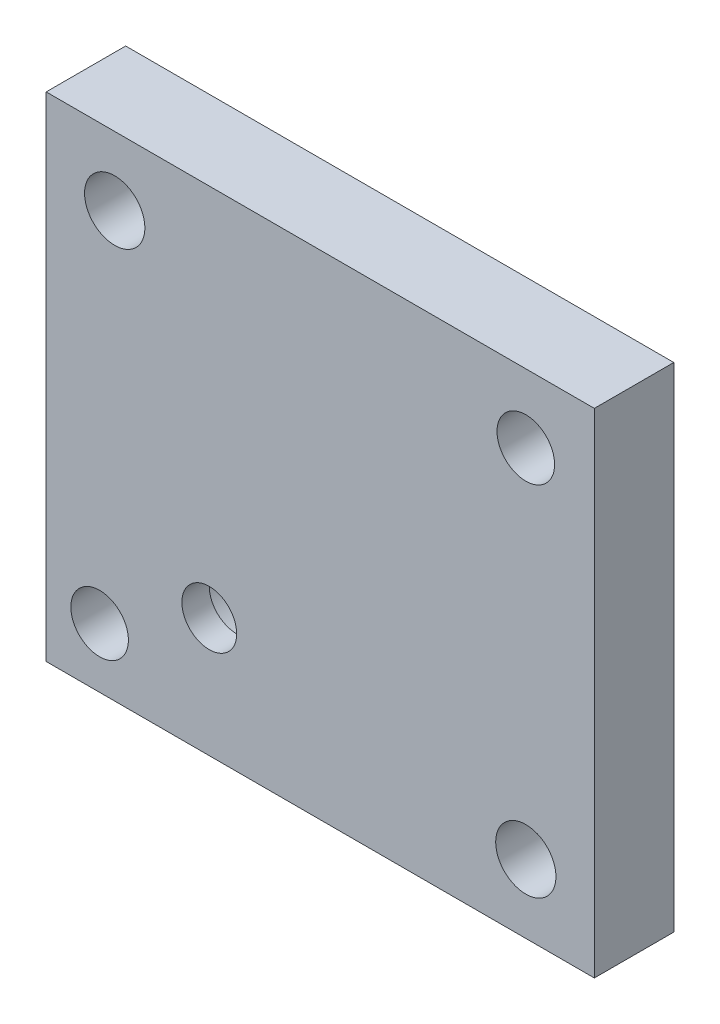
SolidWorks part; units mm, degrees
ref_plane "Front Plane" through (0, 0, 0) normal (0, 0, 1) x (1, 0, 0)
ref_plane "Top Plane" through (0, 0, 0) normal (0, 1, 0) x (1, 0, 0)
ref_plane "Right Plane" through (0, 0, 0) normal (1, 0, 0) x (0, 0, -1)
sketch "Sketch1" plane through (0, 0, 0) normal (0, 0, 1) x (1, 0, 0)
  line L1 (-10, 9) -> (-10, 4) construction
  line L2 (-10, 4) -> (-10, -1.1) construction
  line L3 (-10, -1.1) -> (-10, -9) construction
  line L4 (-10, 9) -> (10, 9)
  line L7 (10, -9) -> (10, 9) construction
  line L9 (-10, 9) -> (-10, 4)
  line L10 (-10, 4) -> (-10, -1.1)
  line L11 (-10, -1.1) -> (-10, -9)
  line L12 (-10, -9) -> (10, -9)
  line L15 (10, -9) -> (10, 9)
  circle A0 centre (7.5, -6.5) radius 1.1 construction
  circle A1 centre (-8.05, -6.825) radius 0.95 construction
  circle A3 centre (-7.5, 6.5) radius 1.1 construction
  circle A4 centre (7.5, 6.5) radius 0.95 construction
  circle A5 centre (7.5, -6.5) radius 1.1
  circle A6 centre (-8.05, -6.825) radius 0.95 construction
  circle A7 centre (-7.5, 6.5) radius 1.1
  circle A9 centre (7.5, 6.5) radius 0.95 construction
  circle A11 centre (-8.05, -6.825) radius 1.05
  circle A13 centre (7.5, 6.5) radius 1.05
  circle A14 centre (-4.05, -4.65) radius 2
  dimension "D1" = 0.1
  dimension "D2" = 4
extrude "Boss-Extrude1" add sketch "Sketch1" along normal blind 1.9
sketch "Sketch2" plane through (0, 0, 1.9) normal (0, 0, 1) x (1, 0, 0)
  line L4 (10, -9) -> (10, 9)
  line L5 (10, 9) -> (-10, 9)
  line L6 (-10, 9) -> (-10, -9)
  line L7 (-10, -9) -> (10, -9)
  line L8 (10, -9) -> (10, 9)
  line L9 (10, 9) -> (-10, 9)
  line L10 (-10, 9) -> (-10, -9)
  line L11 (-10, -9) -> (10, -9)
  circle A0 centre (-7.5, 6.5) radius 1.1 construction
  circle A1 centre (7.5, 6.5) radius 1.05 construction
  circle A2 centre (7.5, -6.5) radius 1.1 construction
  circle A3 centre (-8.05, -6.825) radius 1.05 construction
  circle A4 centre (-7.5, 6.5) radius 1.1
  circle A5 centre (7.5, 6.5) radius 1.05
  circle A6 centre (7.5, -6.5) radius 1.1
  circle A7 centre (-8.05, -6.825) radius 1.05
  circle A8 centre (-4.05, -4.65) radius 1
  dimension "D2" = 2
  dimension "D1" = 0
extrude "Boss-Extrude2" add sketch "Sketch2" along normal blind 1
